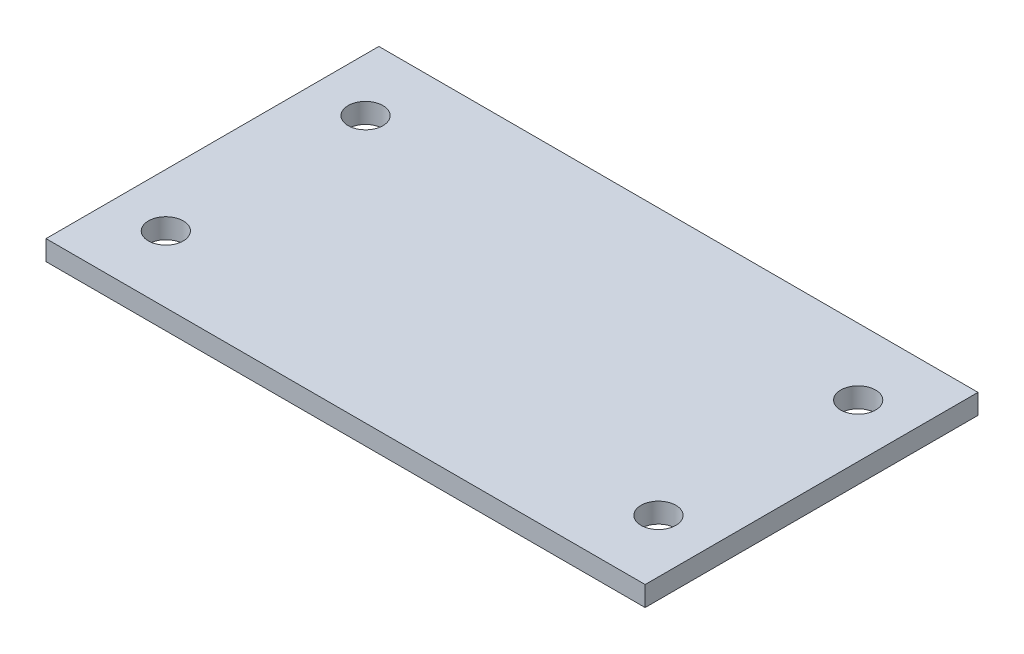
SolidWorks part; units mm, degrees
material "6061 合金"
ref_plane "前视基准面" through (0, 0, 0) normal (0, 0, 1) x (1, 0, 0)
ref_plane "上视基准面" through (0, 0, 0) normal (0, 1, 0) x (1, 0, 0)
ref_plane "右视基准面" through (0, 0, 0) normal (1, 0, 0) x (0, 0, -1)
sketch "草图1" plane through (0, 0, 0) normal (0, 1, 0) x (1, 0, 0)
  line L1 (-45, -25) -> (45, -25)
  line L2 (-45, -25) -> (-45, 25)
  line L3 (-45, 25) -> (45, 25)
  line L4 (45, -25) -> (45, 25)
  line L5 (-45, -25) -> (45, 25) construction
  line L6 (-45, 25) -> (45, -25) construction
  point P0 (0, 0)
  dimension "D1" = 50
  dimension "D2" = 90
extrude "凸台-拉伸1" add sketch "草图1" along normal blind 3 contours L3 L4 L1 L2
sketch "草图2" plane through (0, 0, 0) normal (0, 1, 0) x (1, 0, 0)
  line L0 (-1.65, 0) -> (1.65, 0) construction
  line L1 (0, -1.65) -> (0, 1.65) construction
  circle A0 centre (-37, 15) radius 2.6168
  circle A1 centre (-37, -15) radius 2.6168
  circle A2 centre (37, -15) radius 2.6168
  circle A3 centre (37, 15) radius 2.6168
  dimension "D1" = 37
  dimension "D2" = 15
extrude "切除-拉伸2" cut sketch "草图2" along normal blind 3 and the other way through all
